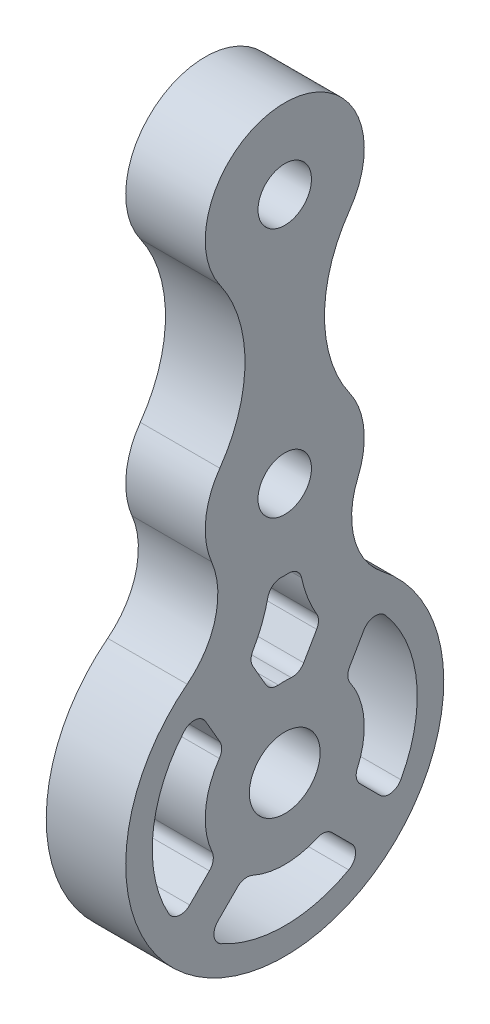
SolidWorks part; units mm, degrees
material "6061 Alloy"
ref_plane "Front Plane" through (0, 0, 0) normal (0, 0, 1) x (1, 0, 0)
ref_plane "Top Plane" through (0, 0, 0) normal (0, 1, 0) x (1, 0, 0)
ref_plane "Right Plane" through (0, 0, 0) normal (1, 0, 0) x (0, 0, -1)
sketch "Sketch1" plane through (0, 0, 0) normal (1, 0, 0) x (0, 0, -1)
  line L0 (0, 0) -> (0, 30) construction
  circle A2 centre (0, 0) radius 2.1209
  circle A3 centre (0, 15) radius 1.6002
  circle A4 centre (0, 30) radius 1.6002
  arc A5 (-3.8902, 27.2528) -> (3.8902, 27.2528) centre (0, 30) cw
  arc A6 (-5.8458, 7.5202) -> (5.8458, 7.5202) centre (0, 0) ccw
  arc A7 (3.8902, 17.7472) -> (4.3843, 13.1401) centre (0, 15) cw
  arc A8 (-3.8902, 17.7472) -> (-4.3843, 13.1401) centre (0, 15) ccw
  arc A9 (-5.8458, 7.5202) -> (-4.3843, 13.1401) centre (-8.7686, 11.2802) ccw
  arc A10 (4.3843, 13.1401) -> (5.8458, 7.5202) centre (8.7686, 11.2802) ccw
  arc A12 (-3.8902, 27.2528) -> (-3.8902, 17.7472) centre (-10.6204, 22.5) cw
  arc A13 (3.8902, 27.2528) -> (3.8902, 17.7472) centre (10.6204, 22.5) ccw
  point P19 (-2.3813, 22.5)
  point P20 (2.3813, 22.5)
  dimension "D2" = 19.05
  dimension "D3" = 3.2004
  dimension "D4" = 4.2418
  dimension "D5" = 4.7625
  dimension "D6" = 4.7625
  dimension "D1" = 30
extrude "Boss-Extrude1" add sketch "Sketch1" along normal blind 4.7625
sketch "Sketch2" plane through (4.7625, 0, 0) normal (1, 0, 0) x (0, 0, -1)
  line L0 (0, 0) -> (0, 10.2375) construction
  line L1 (-2.3813, 4.1244) -> (-4.0557, 7.0246) construction
  line L2 (-3.3676, -3.3676) -> (-5.6127, -5.6127) construction
  line L3 (-6.3911, -4.7073) -> (-4.1026, -2.4188)
  line L4 (-2.4188, -4.1026) -> (-4.7073, -6.3911)
  line L5 (-2.1499, 6.8988) -> (-0.8702, 4.6823)
  line L7 (-3.6199, 3.0948) -> (-0.8702, 4.6823) construction
  line L8 (2.4188, -4.1026) -> (4.7073, -6.3911)
  line L9 (6.3911, -4.7073) -> (4.1026, -2.4188)
  line L11 (2.1499, 6.8988) -> (0.8702, 4.6823)
  line L12 (-3.6199, 3.0948) -> (-5.2634, 5.9414)
  line L13 (3.6199, 3.0948) -> (5.2634, 5.9414)
  arc A0 (5.2634, 5.9414) -> (6.3911, -4.7073) centre (0, 0) cw
  arc A1 (4.3843, 13.1401) -> (3.8902, 17.7472) centre (0, 15) ccw construction
  arc A2 (-0.8893, 10.3213) -> (-2.1499, 6.8988) centre (-8.7686, 11.2802) cw
  arc A3 (0.8893, 10.3213) -> (2.1499, 6.8988) centre (8.7686, 11.2802) ccw
  arc A4 (4.3843, 13.1401) -> (5.8458, 7.5202) centre (8.7686, 11.2802) ccw construction
  arc A9 (-3.6199, 3.0948) -> (-4.1026, -2.4188) centre (0, 0) ccw
  arc A10 (-0.8893, 10.3213) -> (0.8893, 10.3213) centre (0, 15) ccw
  arc A12 (-2.4188, -4.1026) -> (2.4188, -4.1026) centre (0, 0) ccw
  arc A13 (-4.7073, -6.3911) -> (4.7073, -6.3911) centre (0, 0) ccw
  arc A14 (0.8702, 4.6823) -> (-0.8702, 4.6823) centre (0, 0) ccw
  arc A16 (2.9229, 13.7601) -> (4.8715, 6.2668) centre (8.7686, 11.2802) ccw
  arc A17 (2.9229, 13.7601) -> (2.5935, 16.8315) centre (0, 15) ccw
  arc A18 (2.5935, 28.1685) -> (2.5935, 16.8315) centre (10.6204, 22.5) ccw
  arc A19 (2.5935, 28.1685) -> (-2.5935, 28.1685) centre (0, 30) ccw
  arc A20 (-2.5935, 16.8315) -> (-2.5935, 28.1685) centre (-10.6204, 22.5) ccw
  arc A21 (-2.5935, 16.8315) -> (-2.9229, 13.7601) centre (0, 15) ccw
  arc A22 (-4.8715, 6.2668) -> (-2.9229, 13.7601) centre (-8.7686, 11.2802) ccw
  arc A23 (-4.8715, 6.2668) -> (4.8715, 6.2668) centre (0, 0) ccw
  arc A31 (-5.2634, 5.9414) -> (-6.3911, -4.7073) centre (0, 0) ccw
  arc A32 (4.1026, -2.4188) -> (3.6199, 3.0948) centre (0, 0) ccw
  point P0 (2.062, 7.0246)
  point P17 (-2.2451, 3.8886)
  dimension "D2" = 9.525
  dimension "D3" = 3.175
  dimension "D4" = 135
  dimension "D5" = 30
  dimension "D6" = 2.3813
  dimension "D7" = 3.175
  dimension "D1" = 1.5875
extrude "Cut-Extrude1" cut sketch "Sketch2" against normal through all
fillet "Fillet1" radius 0.7937 18 edges at (2.3813, 4.6823, -0.8702) (2.3813, -4.1026, -2.4188) (2.3813, -6.3911, -4.7073) (2.3813, -4.7073, -6.3911) (2.3813, -2.4188, -4.1026) (2.3813, 3.0948, -3.6199) (2.3813, 5.9414, -5.2634) (2.3813, -4.1026, 2.4188) (2.3813, -6.3911, 4.7073) (2.3813, -4.7073, 6.3911) (2.3813, -2.4188, 4.1026) (2.3813, 5.9414, 5.2634) (2.3813, 3.0948, 3.6199) (2.3813, 4.6823, 0.8702) (2.3813, 6.8988, -2.1499) (2.3813, 6.8988, 2.1499) (2.3813, 10.3213, 0.8893) (2.3813, 10.3213, -0.8893)
